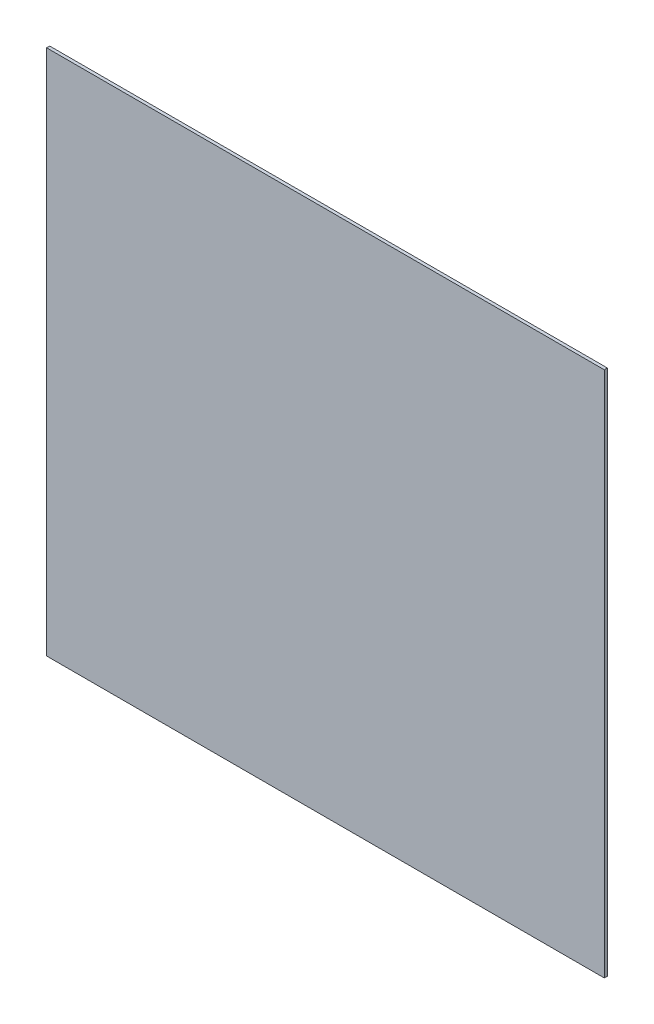
SolidWorks part; units mm, degrees
ref_plane "Front Plane" through (0, 0, 0) normal (0, 0, 1) x (1, 0, 0)
ref_plane "Top Plane" through (0, 0, 0) normal (0, 1, 0) x (1, 0, 0)
ref_plane "Right Plane" through (0, 0, 0) normal (1, 0, 0) x (0, 0, -1)
sketch "Sketch1" plane through (0, 0, 0) normal (0, 0, 1) x (1, 0, 0)
  line L1 (270, 255) -> (-270, 255)
  line L2 (270, 255) -> (270, -255)
  line L3 (270, -255) -> (-270, -255)
  line L4 (-270, 255) -> (-270, -255)
  line L5 (270, 255) -> (-270, -255) construction
  line L6 (270, -255) -> (-270, 255) construction
  point P0 (0, 0)
  dimension "D1" = 540
  dimension "D2" = 510
extrude "Boss-Extrude1" add sketch "Sketch1" along normal blind 3
